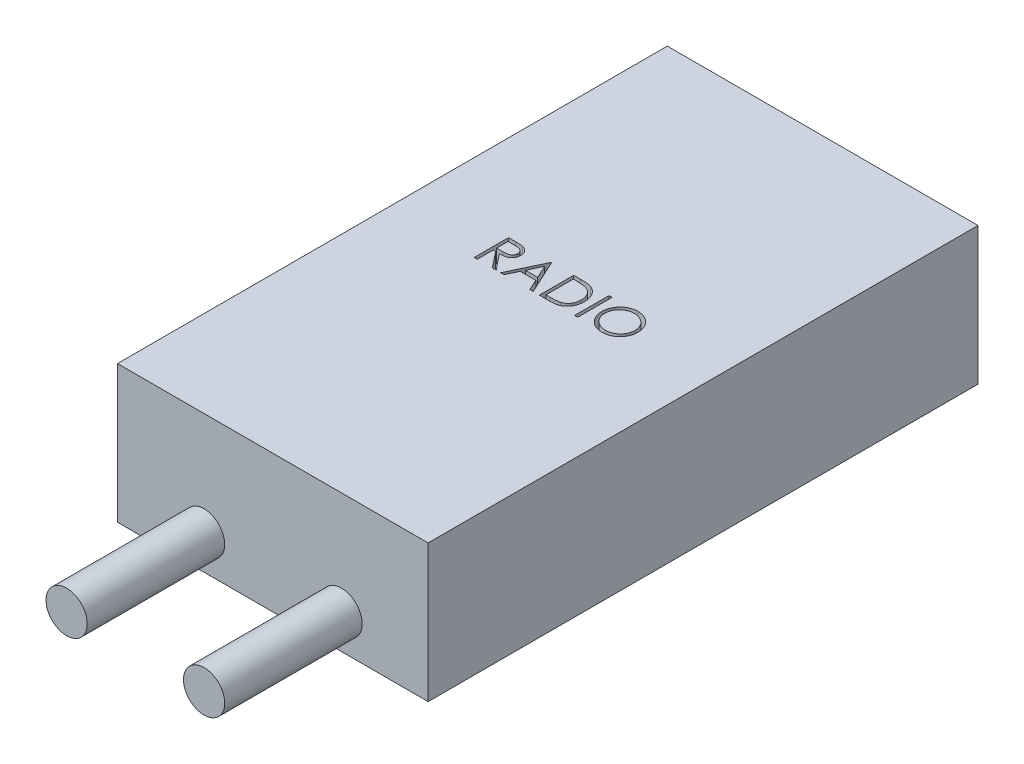
SolidWorks part; units mm, degrees
ref_plane "Front Plane" through (0, 0, 0) normal (0, 0, 1) x (1, 0, 0)
ref_plane "Top Plane" through (0, 0, 0) normal (0, 1, 0) x (1, 0, 0)
ref_plane "Right Plane" through (0, 0, 0) normal (1, 0, 0) x (0, 0, -1)
sketch "Sketch1" plane through (0, 0, 0) normal (0, 1, 0) x (1, 0, 0)
  line L1 (-14.351, -25.4) -> (14.351, -25.4)
  line L2 (-14.351, -25.4) -> (-14.351, 25.4)
  line L3 (-14.351, 25.4) -> (14.351, 25.4)
  line L4 (14.351, -25.4) -> (14.351, 25.4)
  line L5 (-14.351, -25.4) -> (14.351, 25.4) construction
  line L6 (-14.351, 25.4) -> (14.351, -25.4) construction
  point P0 (0, 0)
  dimension "D1" = 50.8
  dimension "D2" = 28.702
extrude "Boss-Extrude1" add sketch "Sketch1" along normal blind 12.7
sketch "Sketch2" plane through (0, 0, 25.4) normal (0, 0, 1) x (1, 0, 0)
  line L0 (0, 0) -> (0, 8.1729) construction
  line L1 (-14.351, 0) -> (14.351, 0) construction
  circle A0 centre (-6.35, 3.175) radius 1.905
  circle A1 centre (6.35, 3.175) radius 1.905
  dimension "D1" = 3.81
  dimension "D2" = 6.35
  dimension "D3" = 3.175
extrude "Boss-Extrude2" add sketch "Sketch2" along normal blind 12.7
sketch "Sketch3" plane through (0, 12.7, 0) normal (0, 1, 0) x (1, 0, 0)
  text T0 "RADIO"
extrude "Cut-Extrude1" cut sketch "Sketch3" against normal blind 1.27
equation "\"D1@Sketch1\"=\"Radio Rx Y@Quad Assemb.sldasm\""
equation "\"D2@Sketch1\"=\"Radio Rx X@Quad Assemb.sldasm\""
equation "\"D1@Boss-Extrude1\"=\"Radio Rx Z@Quad Assemb.sldasm\""
